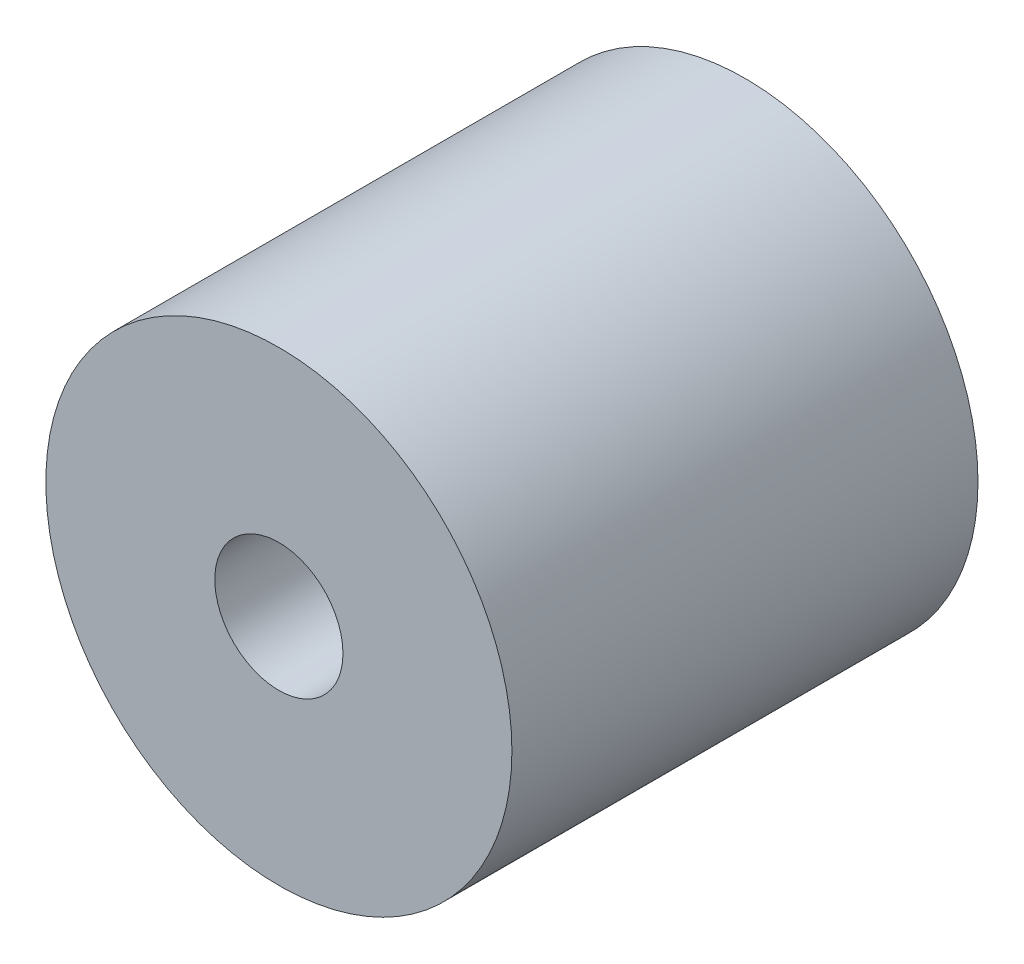
SolidWorks part; units mm, degrees
ref_plane "前视基准面" through (0, 0, 0) normal (0, 0, 1) x (1, 0, 0)
ref_plane "上视基准面" through (0, 0, 0) normal (0, 1, 0) x (1, 0, 0)
ref_plane "右视基准面" through (0, 0, 0) normal (1, 0, 0) x (0, 0, -1)
sketch "草图1" plane through (0, 0, 0) normal (0, 0, 1) x (1, 0, 0)
  circle A0 centre (0, 0) radius 1.1
  circle A1 centre (0, 0) radius 4
  dimension "D1" = 2.2
  dimension "D2" = 8
extrude "凸台-拉伸1" add sketch "草图1" along normal blind 8
